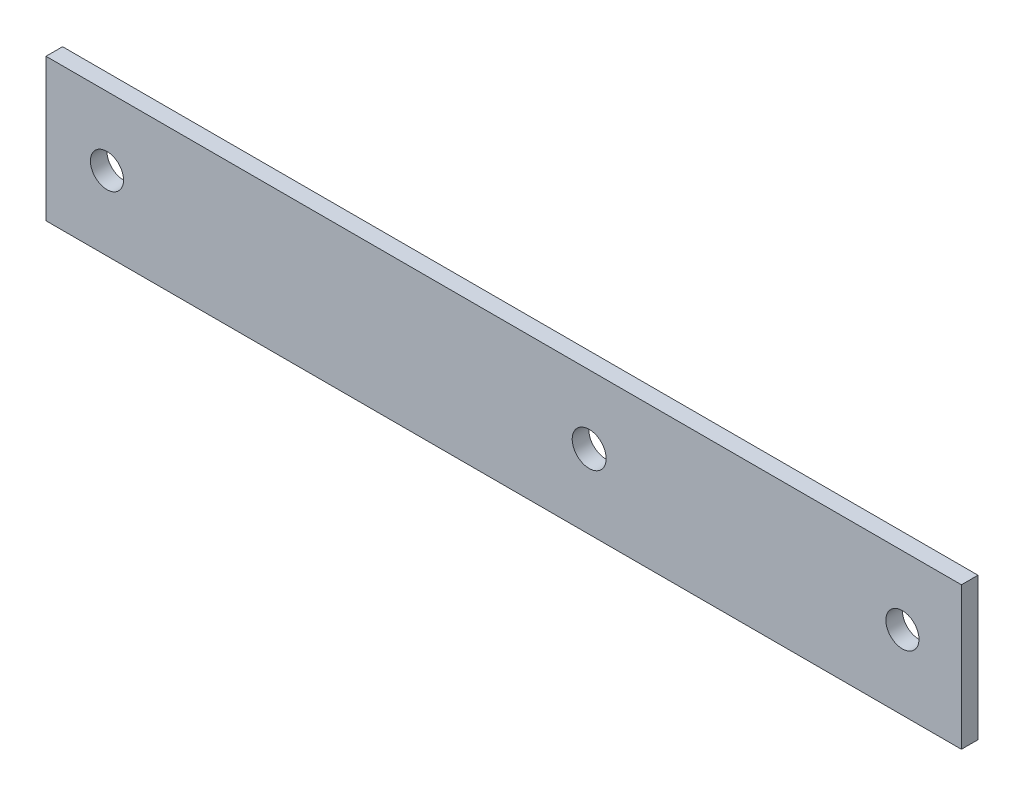
SolidWorks part; units mm, degrees
ref_plane "Front Plane" through (0, 0, 0) normal (0, 0, 1) x (1, 0, 0)
ref_plane "Top Plane" through (0, 0, 0) normal (0, 1, 0) x (1, 0, 0)
ref_plane "Right Plane" through (0, 0, 0) normal (1, 0, 0) x (0, 0, -1)
sketch "Sketch1" plane through (0, 0, 0) normal (0, 0, 1) x (1, 0, 0)
  line L1 (64.5184, 13.1181) -> (239.9091, 13.1181)
  line L2 (64.5184, 13.1181) -> (64.5184, -14.1841)
  line L3 (64.5184, -14.1841) -> (239.9091, -14.1841)
  line L4 (239.9091, 13.1181) -> (239.9091, -14.1841)
  circle A0 centre (76.2, 0) radius 3.175
  circle A1 centre (228.6, 0) radius 3.175
  circle A2 centre (168.5885, 0) radius 3.2512
  circle A3 centre (168.5885, 0) radius 3.175 construction
  dimension "D1" = 6.5024
  dimension "D2" = 6.35
  dimension "D3" = 6.35
extrude "Boss-Extrude1" add sketch "Sketch1" along normal blind 3.175
